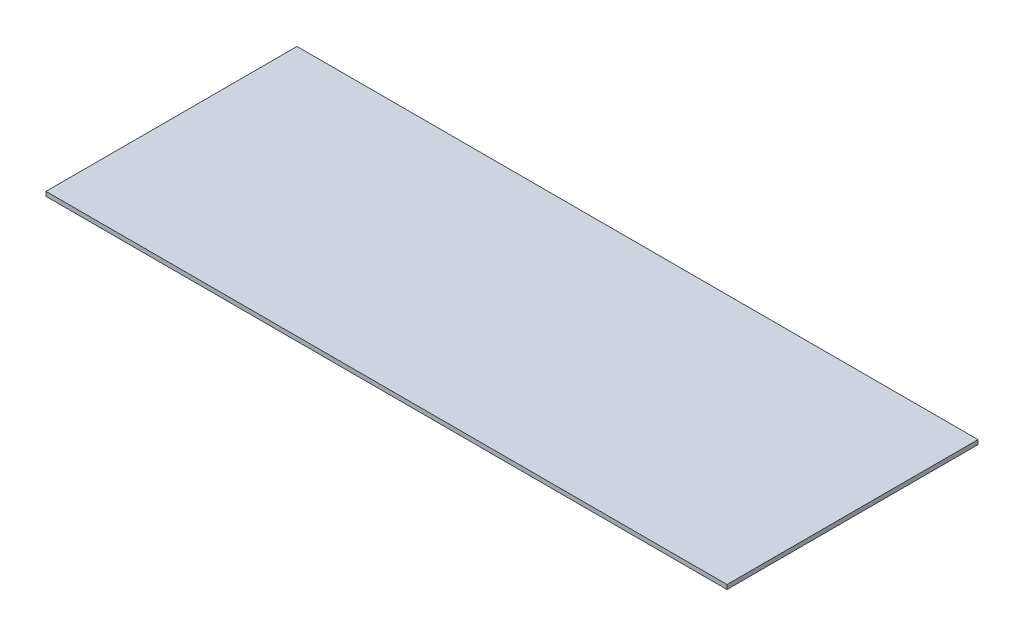
SolidWorks part; units mm, degrees
ref_plane "Front Plane" through (0, 0, 0) normal (0, 0, 1) x (1, 0, 0)
ref_plane "Top Plane" through (0, 0, 0) normal (0, 1, 0) x (1, 0, 0)
ref_plane "Right Plane" through (0, 0, 0) normal (1, 0, 0) x (0, 0, -1)
sketch "Sketch1" plane through (0, 0, 0) normal (0, 1, 0) x (1, 0, 0)
  line L1 (0, 0) -> (312, 0)
  line L2 (0, 0) -> (0, 115)
  line L3 (0, 115) -> (312, 115)
  line L4 (312, 0) -> (312, 115)
  dimension "D1" = 312
  dimension "D2" = 115
extrude "Boss-Extrude1" add sketch "Sketch1" along normal blind 2
